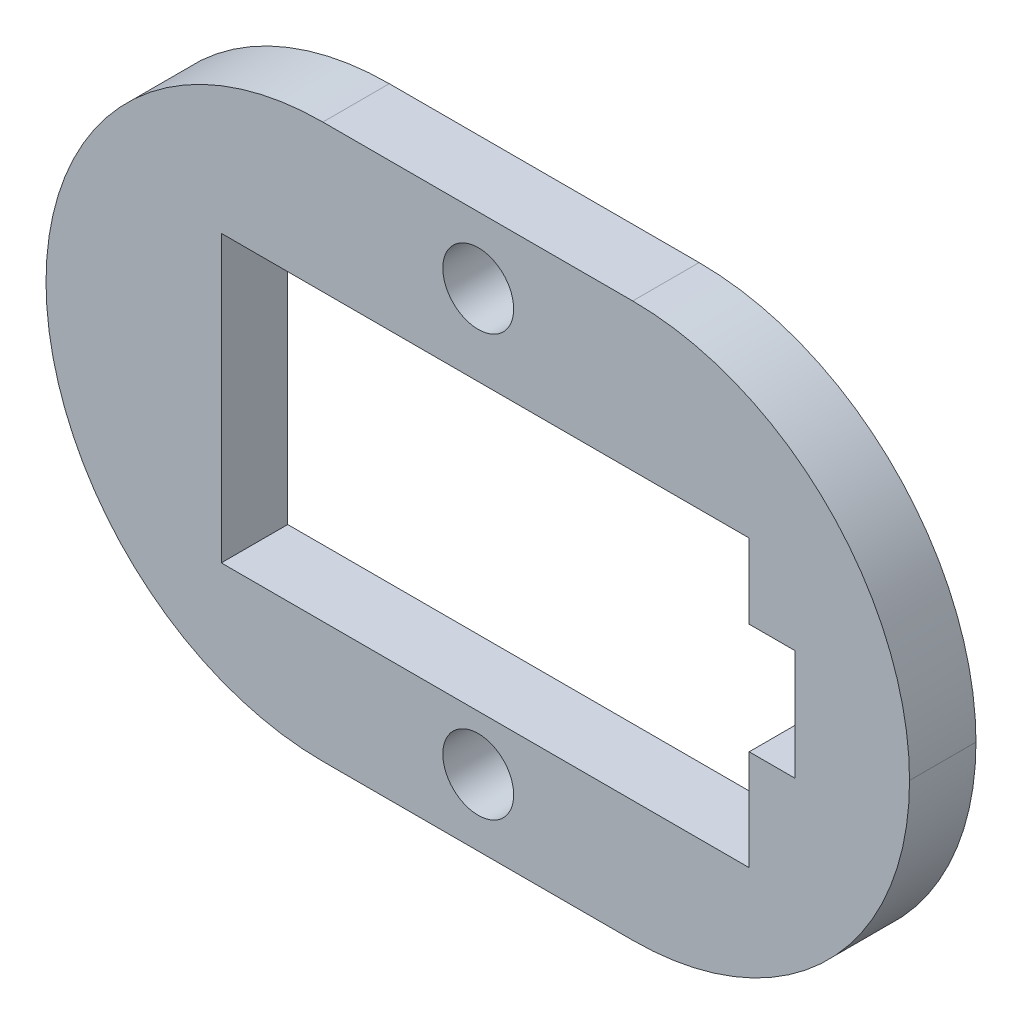
SolidWorks part; units mm, degrees
ref_plane "前视基准面" through (0, 0, 0) normal (0, 0, 1) x (1, 0, 0)
ref_plane "上视基准面" through (0, 0, 0) normal (0, 1, 0) x (1, 0, 0)
ref_plane "右视基准面" through (0, 0, 0) normal (1, 0, 0) x (0, 0, -1)
ref_plane "基准面4" through (0, 0, 0) normal (0, 0, -1) x (-1, 0, 0)
sketch "草图1" plane through (0, 0, 0) normal (0, 0, -1) x (-1, 0, 0)
  line L0 (-12.8054, 14.9897) -> (-10.7446, 14.9897)
  line L1 (-10.7446, 14.9897) -> (-10.7446, 18.3586)
  line L2 (-10.7446, 18.3586) -> (13.0892, 18.3586)
  line L3 (13.0892, 18.3586) -> (13.0892, 5.4702)
  line L4 (13.0892, 5.4702) -> (-10.7446, 5.4702)
  line L5 (-10.7446, 5.4702) -> (-10.7446, 10.001)
  line L6 (-10.7446, 10.001) -> (-12.8054, 10.001)
  line L7 (-12.8054, 10.001) -> (-12.8054, 14.9897)
  line L8 (8.5033, 25.001) -> (-5.4866, 25.001)
  line L9 (-17.9866, 12.501) -> (-17.9866, 12.5)
  line L10 (-5.4866, 0) -> (8.5033, 0)
  arc A0 (8.5033, 0) -> (21.0033, 12.5) centre (8.5033, 12.5) ccw
  arc A1 (21.0033, 12.5) -> (8.5033, 25.001) centre (8.5033, 12.501) ccw
  arc A2 (-5.4866, 25.001) -> (-17.9866, 12.501) centre (-5.4866, 12.501) ccw
  arc A3 (-17.9866, 12.5) -> (-5.4866, 0) centre (-5.4866, 12.5) ccw
  circle A4 centre (1.4879, 21.9995) radius 1.3
  circle A5 centre (1.4879, 2.9995) radius 1.3
  dimension "D1" = 19
extrude "凸台-拉伸1" add sketch "草图1" against normal blind 3
sketch "草图2" plane through (0, 0, 3) normal (0, 0, 1) x (1, 0, 0)
  circle A0 centre (-1.4879, 21.9995) radius 1.6
  circle A1 centre (-1.4879, 2.9995) radius 1.6
  dimension "D1" = 3.2
extrude "切除-拉伸1" cut sketch "草图2" against normal through all
chamfer "倒角1" distance 0.3 angle 45 2 edges at (0.1121, 2.9995, 0) (0.1121, 21.9995, 0)
